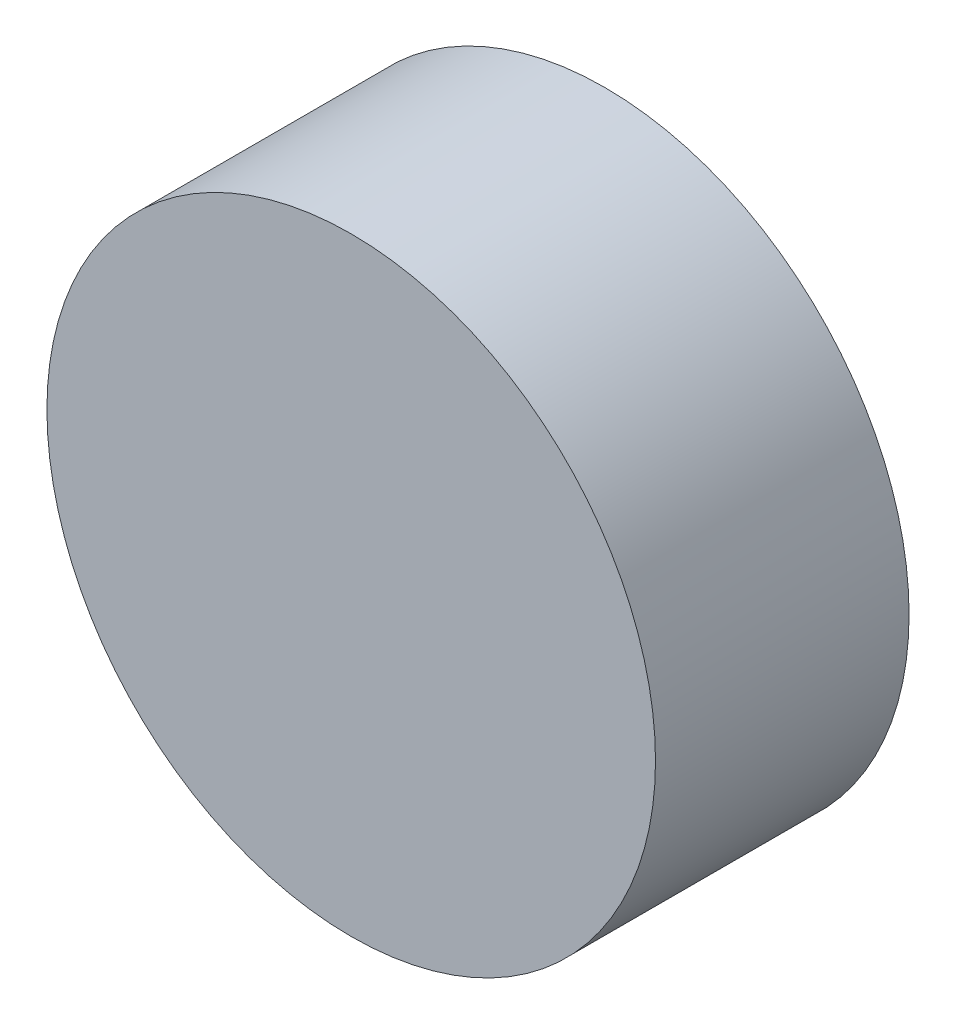
SolidWorks part; units mm, degrees
ref_plane "Alzado" through (0, 0, 0) normal (0, 0, 1) x (1, 0, 0)
ref_plane "Planta" through (0, 0, 0) normal (0, 1, 0) x (1, 0, 0)
ref_plane "Vista lateral" through (0, 0, 0) normal (1, 0, 0) x (0, 0, -1)
sketch "Croquis1" plane through (0, 0, 0) normal (0, 0, 1) x (1, 0, 0)
  circle A0 centre (0, 0) radius 3
extrude "Saliente-Extruir1" add sketch "Croquis1" along normal blind 2.5
